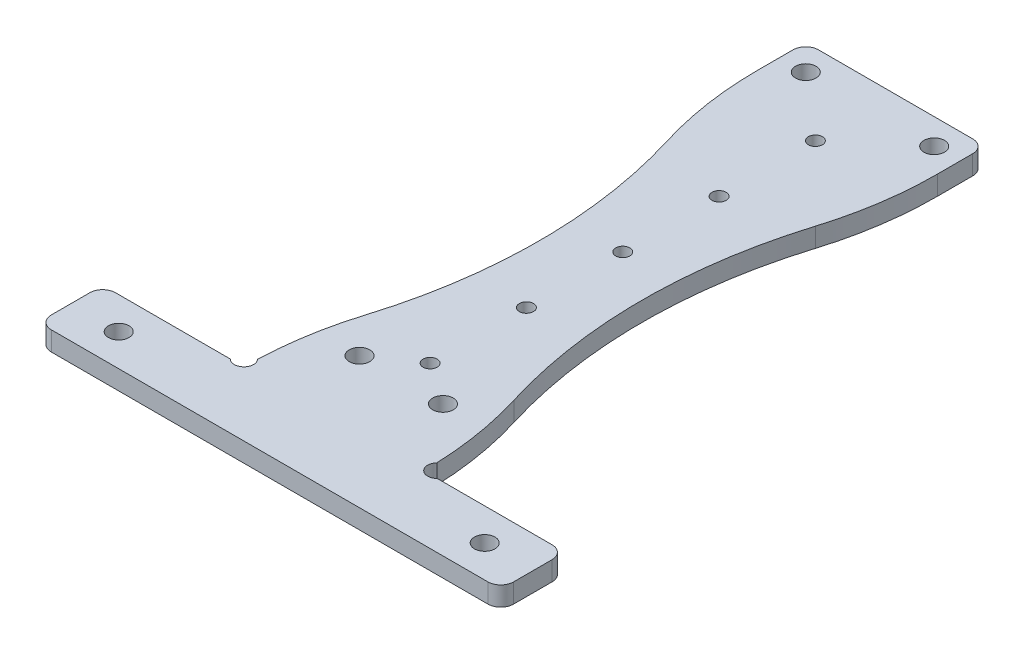
SolidWorks part; units mm, degrees
material "碳板"
ref_plane "前视基准面" through (0, 0, 0) normal (0, 0, 1) x (1, 0, 0)
ref_plane "上视基准面" through (0, 0, 0) normal (0, 1, 0) x (1, 0, 0)
ref_plane "右视基准面" through (0, 0, 0) normal (1, 0, 0) x (0, 0, -1)
sketch "草图1" plane through (0, 0, 0) normal (0, 1, 0) x (1, 0, 0)
  line L0 (-56.2892, 0) -> (60.3373, 0) construction
  line L1 (0, 67.9518) -> (0, -47.5181) construction
  line L2 (-36, 0) -> (36, 0)
  line L3 (36, 0) -> (36, 10)
  line L4 (36, 10) -> (14, 10)
  line L5 (14, 10) -> (14, 97.5)
  line L6 (14, 97.5) -> (-14, 97.5)
  line L7 (-14, 10) -> (-14, 97.5)
  line L8 (-36, 10) -> (-14, 10)
  line L9 (-36, 0) -> (-36, 10)
  line L10 (-47.8239, 90) -> (15.5045, 90) construction
  line L11 (-15.0607, 11.0607) -> (-14, 10) construction
  line L12 (0, 85) -> (0, 70) construction
  line L13 (-88, 50) -> (-8, 50) construction
  line L14 (88, 50) -> (8, 50) construction
  circle A0 centre (10, 93.5) radius 1.6
  circle A1 centre (-10, 93.5) radius 1.6
  circle A2 centre (28.5, 5) radius 1.6
  circle A3 centre (-28.5, 5) radius 1.6
  circle A4 centre (-15.0607, 11.0607) radius 1.5
  circle A5 centre (15.0607, 11.0607) radius 1.5
  circle A6 centre (0, 85) radius 1.1
  circle A7 centre (0, 70) radius 1.1
  circle A8 centre (0, 55) radius 1.1
  circle A9 centre (0, 40) radius 1.1
  circle A10 centre (0, 25) radius 1.1
  arc A11 (-14, 90) -> (-11.5208, 73.4719) centre (42.3333, 90) ccw
  arc A12 (-11.5208, 73.4719) -> (-11.5208, 26.5281) centre (-88, 50) cw
  arc A13 (-11.5208, 26.5281) -> (-14, 10) centre (42.3333, 10) ccw
  arc A14 (11.5208, 26.5281) -> (14, 10) centre (-42.3333, 10) cw
  arc A15 (11.5208, 73.4719) -> (11.5208, 26.5281) centre (88, 50) ccw
  arc A16 (14, 90) -> (11.5208, 73.4719) centre (-42.3333, 90) cw
  circle A17 centre (-6.5, 20.5) radius 1.6
  circle A18 centre (6.5, 20.5) radius 1.6
  point P12 (0, 97.5)
  point P15 (0, 0)
  dimension "D1" = 3.2
  dimension "D7" = 57
  dimension "D11" = 3
  dimension "D13" = 2.2
  dimension "D17" = 16
  dimension "D18" = 80
  dimension "D20" = 77
  dimension "D2" = 20
  dimension "D3" = 4
  dimension "D4" = 4
  dimension "D5" = 7.5
  dimension "D6" = 80
  dimension "D8" = 7.5
  dimension "D9" = 5
  dimension "D10" = 10
  dimension "D12" = 45
  dimension "D14" = 5
  dimension "D16" = 15
  dimension "D19" = 80
  dimension "D21" = 13
  dimension "D15" = 5
extrude "凸台-拉伸1" add sketch "草图1" along normal blind 3 contours A16 L5 L6 L7 A11 A12 A13 A4 L8 L9 L2 L3 L4 A5 A14 A15 A10 A9 A8 A7 A6 A1 A0 A2 A3
fillet "圆角1" radius 2 6 edges at (36, 1.5, -10) (36, 1.5, 0) (-36, 1.5, 0) (-36, 1.5, -10) (-14, 1.5, -97.5) (14, 1.5, -97.5)
